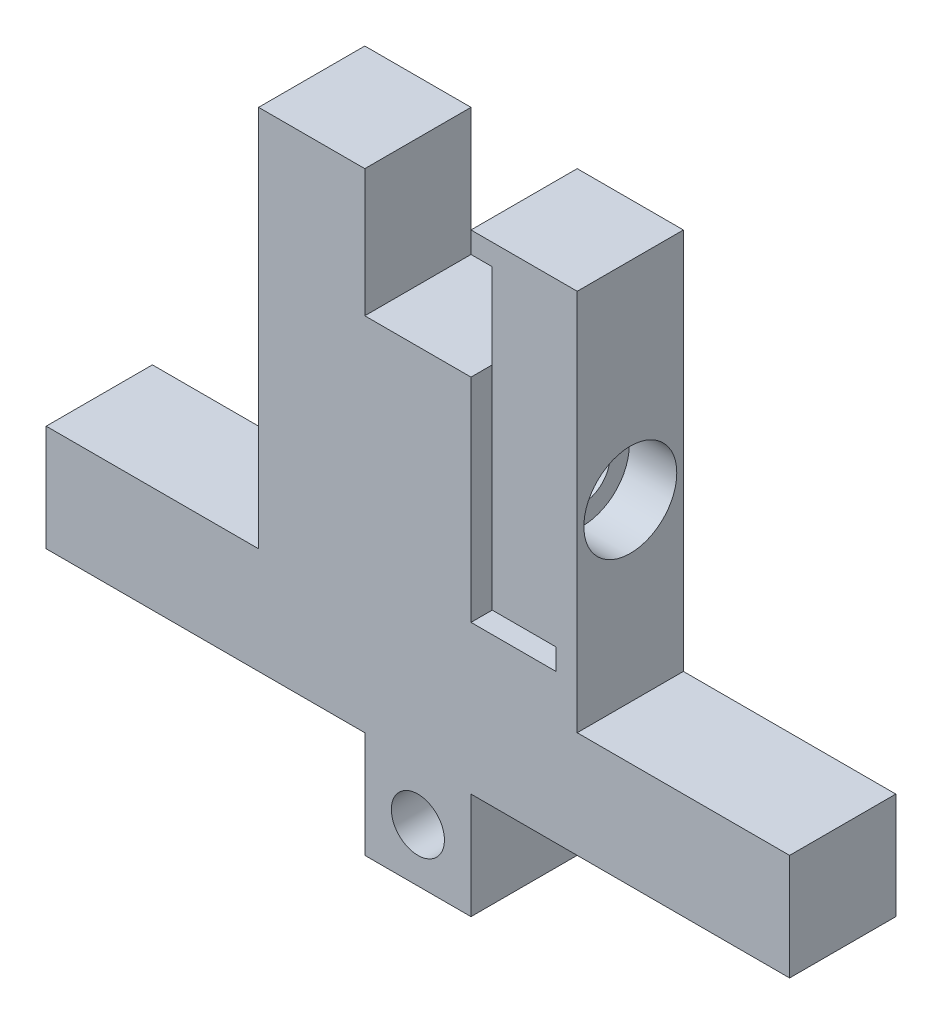
SolidWorks part; units mm, degrees
material "6061 Alloy"
ref_plane "Front Plane" through (0, 0, 0) normal (0, 0, 1) x (1, 0, 0)
ref_plane "Top Plane" through (0, 0, 0) normal (0, 1, 0) x (1, 0, 0)
ref_plane "Right Plane" through (0, 0, 0) normal (1, 0, 0) x (0, 0, -1)
sketch "Sketch2" plane through (0, 0, 0) normal (0, 0, 1) x (1, 0, 0)
  line L1 (-9.525, -15.875) -> (9.525, -15.875)
  line L2 (-9.525, -15.875) -> (-9.525, 15.875)
  line L3 (-9.525, 15.875) -> (9.525, 15.875)
  line L4 (9.525, -15.875) -> (9.525, 15.875)
  line L5 (-9.525, -15.875) -> (9.525, 15.875) construction
  line L6 (-9.525, 15.875) -> (9.525, -15.875) construction
  point P0 (0, 0)
  dimension "D1" = 31.75
  dimension "D2" = 19.05
extrude "Boss-Extrude1" add sketch "Sketch2" along normal mid plane 6.35
sketch "Sketch4" plane through (-1.5069, 3.1105, 3.175) normal (0, 0, 1) x (1, 0, 0)
  line L1 (-1.6681, 12.7645) -> (4.6819, 12.7645)
  line L2 (-1.6681, 12.7645) -> (-1.6681, 2.6045)
  line L3 (-1.6681, 2.6045) -> (4.6819, 2.6045)
  line L4 (4.6819, 12.7645) -> (4.6819, 2.6045)
  line L7 (-8.0181, 12.7645) -> (11.0319, 12.7645)
  line L8 (-8.0181, 12.7645) -> (-8.0181, 10.2245)
  line L9 (-8.0181, 10.2245) -> (11.0319, 10.2245)
  line L10 (11.0319, 12.7645) -> (11.0319, 10.2245)
  line L11 (11.0319, 12.7645) -> (-8.0181, 12.7645) construction
  line L12 (11.0319, -18.9855) -> (11.0319, 12.7645) construction
  line L13 (-8.0181, 12.7645) -> (-8.0181, -18.9855) construction
  dimension "D1" = 6.35
  dimension "D2" = 0
  dimension "D3" = 10.16
  dimension "D4" = 2.54
  dimension "D5" = 0
  dimension "D6" = 0
  dimension "D7" = 0
  dimension "D8" = 6.35
extrude "Cut-Extrude1" cut sketch "Sketch4" against normal through all
sketch "Sketch6" plane through (-1.5069, 3.1105, 3.175) normal (0, 0, 1) x (1, 0, 0)
  line L0 (4.6819, 10.2245) -> (4.6819, 2.6045) construction
  line L5 (4.6819, 8.9545) -> (5.9519, 8.9545)
  line L6 (4.6819, 8.9545) -> (4.6819, -10.0955)
  line L7 (4.6819, -10.0955) -> (5.9519, -10.0955)
  line L8 (5.9519, 8.9545) -> (5.9519, -10.0955)
  line L12 (4.6819, -10.0955) -> (9.7619, -10.0955)
  line L13 (4.6819, -10.0955) -> (4.6819, -8.8255)
  line L14 (4.6819, -8.8255) -> (9.7619, -8.8255)
  line L15 (9.7619, -10.0955) -> (9.7619, -8.8255)
  line L16 (4.6819, 10.2245) -> (11.0319, 10.2245) construction
  line L17 (-8.0181, -18.9855) -> (11.0319, -18.9855) construction
  line L18 (11.0319, -18.9855) -> (11.0319, 10.2245) construction
  point P7 (5.3169, -10.0955)
  dimension "D1" = 1.27
  dimension "D2" = 1.27
  dimension "D3" = 8.89
  dimension "D4" = 1.27
  dimension "D5" = 1.27
extrude "Cut-Extrude2" cut sketch "Sketch6" against normal through all
hole_wizard "CBORE for #4 Socket Head Cap Screw1" positions "Sketch15" profile "Sketch16" counterbore size "#4" standard "ANSI Inch"
sketch "Sketch15" plane through (9.525, 0, 0) normal (1, 0, 0) x (0, 0, -1)
  line L1 (3.175, -15.875) -> (3.175, 13.335) construction
  point P8 (0, 0.9525)
  dimension "D1" = 4.7625
  dimension "D2" = 3.175
sketch "Sketch16" plane through (9.525, 0.9525, 0) normal (0, 1, 0) x (0, 0, -1)
  line L0 (0, 0) -> (0, 5.08)
  line L1 (0, 5.08) -> (1.6319, 5.08)
  line L3 (1.6319, 5.08) -> (1.6319, 2.8448)
  line L4 (1.6319, 2.8448) -> (2.7788, 2.8448)
  line L5 (2.7788, 2.8448) -> (2.7788, 0)
  line L7 (2.7788, 0) -> (0, 0)
  line L11 (0, -6.35) -> (0, 107.95) construction
  dimension "Thru Hole Dia." = 3.2639
  dimension "Thru Hole Depth" = 5.08
  dimension "C'Bore Dia." = 5.5575
  dimension "C'Bore Depth" = 2.8448
hole_wizard "#4-40 Tapped Hole1" positions "Sketch17" profile "Sketch19" tap size "#4-40" standard "ANSI Inch" end condition through all
sketch "Sketch17" plane through (3.175, 0, 0) normal (1, 0, 0) x (0, 0, -1)
  line L0 (3.175, 5.715) -> (-3.175, 5.715) construction
  line L1 (-3.175, 5.715) -> (-3.175, -6.985) construction
  point P0 (0, 0.9525)
  dimension "D1" = 4.7625
  dimension "D2" = 3.175
sketch "Sketch19" plane through (3.175, 0.9525, 0) normal (0, 1, 0) x (0, 0, -1)
  line L0 (0, 0) -> (0, 12.7)
  line L1 (0, 12.7) -> (1.1303, 12.7)
  line L2 (1.1303, 12.7) -> (1.1303, 0)
  line L5 (1.1303, 0) -> (0, 0)
  line L11 (0, -6.35) -> (0, 107.95) construction
  dimension "Thru Tap Drill Dia." = 2.2606
  dimension "Thru Tap Drill Depth" = 12.7
cosmetic thread "Hole Thread5" parameters "D2"=2.8448
sketch "Sketch20" plane through (0, 0, 3.175) normal (0, 0, 1) x (1, 0, 0)
  line L1 (9.525, -15.875) -> (22.225, -15.875)
  line L2 (9.525, -15.875) -> (9.525, -9.525)
  line L3 (9.525, -9.525) -> (22.225, -9.525)
  line L4 (22.225, -15.875) -> (22.225, -9.525)
  dimension "D1" = 12.7
  dimension "D2" = 6.35
extrude "Boss-Extrude2" add sketch "Sketch20" against normal through all
mirror "Mirror1" about plane through (0, 0, 0) normal (1, 0, 0) of "Boss-Extrude2"
sketch "Sketch21" plane through (0, 0, -3.175) normal (0, 0, -1) x (-1, 0, 0)
  line L0 (22.225, -15.875) -> (-22.225, -15.875) construction
  line L1 (-3.175, -9.525) -> (3.175, -9.525)
  line L2 (-3.175, -9.525) -> (-3.175, -22.225)
  line L3 (-3.175, -22.225) -> (3.175, -22.225)
  line L4 (3.175, -9.525) -> (3.175, -22.225)
  line L5 (-3.175, -9.525) -> (3.175, -22.225) construction
  line L6 (-3.175, -22.225) -> (3.175, -9.525) construction
  point P0 (0, -15.875)
  dimension "D1" = 6.35
  dimension "D2" = 6.35
extrude "Boss-Extrude4" add sketch "Sketch21" against normal through all
sketch "Sketch22" plane through (0, 0, -3.175) normal (0, 0, -1) x (-1, 0, 0)
  line L0 (-3.175, -22.225) -> (3.175, -22.225) construction
  line L1 (-3.175, -15.875) -> (-3.175, -22.225) construction
  circle A0 centre (0, -19.05) radius 1.5875
  dimension "D3" = 3.175
  dimension "D1" = 3.175
  dimension "D2" = 3.175
extrude "Cut-Extrude3" cut sketch "Sketch22" against normal through all
